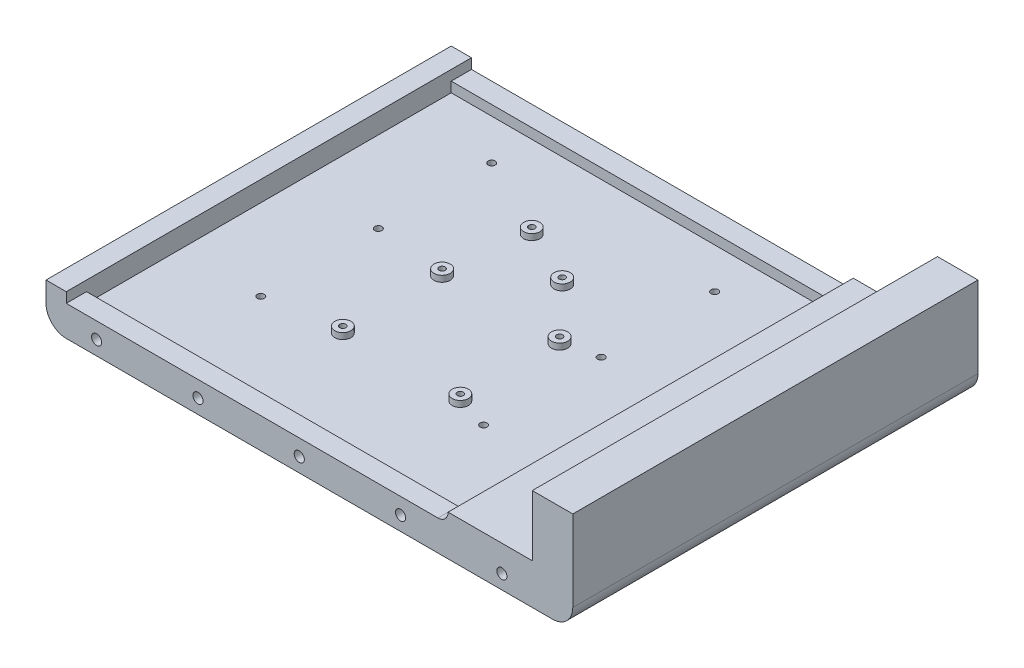
SolidWorks part; units mm, degrees
ref_plane "前视基准面" through (0, 0, 0) normal (0, 0, 1) x (1, 0, 0)
ref_plane "上视基准面" through (0, 0, 0) normal (0, 1, 0) x (1, 0, 0)
ref_plane "右视基准面" through (0, 0, 0) normal (1, 0, 0) x (0, 0, -1)
other "Configuration Table"
sketch "草图1" plane through (0, 0, 0) normal (0, 0, 1) x (1, 0, 0)
  line L0 (-120, 0) -> (120, 0)
  line L1 (130, 10) -> (130, 49.9853)
  line L3 (-130, 20) -> (-130, 10)
  line L6 (-110, 20) -> (110, 20)
  line L7 (110, 20) -> (110, 48.0385)
  line L10 (-110, 20) -> (-130, 20)
  line L11 (130, 49.9853) -> (130, 50)
  line L20 (130, 50) -> (110, 50)
  line L21 (110, 50) -> (110, 48.0385)
  arc A1 (-120, 0) -> (-130, 10) centre (-120, 10) cw
  arc A2 (120, 0) -> (130, 10) centre (120, 10) ccw
  point P15 (0, 0)
  dimension "D2" = 260
  dimension "D3" = 10
  dimension "D4" = 10
  dimension "D5" = 20
  dimension "D1" = 50
extrude "凸台-拉伸1" add sketch "草图1" along normal blind 200
sketch "草图3" plane through (0, 0, 200) normal (0, 0, 1) x (1, 0, 0)
  line L14 (-120, 20) -> (68.453, 20)
  line L15 (-115, 15) -> (120, 15)
  line L16 (-115, 20) -> (-115, 15)
  line L17 (-120, 15) -> (63.453, 15)
  line L18 (130, 10) -> (130, 50) construction
  line L19 (110, 20) -> (-130, 20) construction
  line L20 (-130, 20) -> (-130, 10) construction
  line L21 (-120, 15) -> (-120, 20)
  arc A10 (68.453, 20) -> (63.453, 15) centre (63.453, 20) cw
  dimension "D2" = 10
  dimension "D3" = 61.547
  dimension "D4" = 5
  dimension "D1" = 15
extrude "切除-拉伸1" cut sketch "草图3" against normal up to next
sketch "草图4" plane through (0, 15, 0) normal (0, 1, 0) x (1, 0, 0)
  line L0 (30, -30) -> (-80, -30) construction
  line L1 (-80, -30) -> (-80, -86) construction
  line L2 (-80, -86) -> (30, -86) construction
  line L3 (30, -86) -> (30, -30) construction
  line L4 (-80, -86) -> (-80, -144) construction
  line L5 (-80, -144) -> (30, -144) construction
  line L6 (30, -144) -> (30, -86) construction
  line L7 (13.911, -90.416) -> (-44.089, -90.416) construction
  line L8 (-44.089, -90.416) -> (-44.089, -139.416) construction
  line L9 (-44.089, -139.416) -> (13.911, -139.416) construction
  line L10 (13.911, -139.416) -> (13.911, -90.416) construction
  line L11 (-120, 0) -> (63.453, 0) construction
  line L13 (-130, -200) -> (-130, 0) construction
  circle A27 centre (30, -30) radius 1.75
  circle A29 centre (30, -86) radius 1.75
  circle A30 centre (30, -144) radius 1.75
  circle A31 centre (-80, -144) radius 1.75
  circle A32 centre (-80, -86) radius 1.75
  circle A33 centre (-80, -30) radius 1.75
  circle A34 centre (-10.76, -64.486) radius 1.5
  circle A35 centre (-39.76, -50.486) radius 1.5
  circle A36 centre (-44.089, -90.416) radius 1.5
  circle A37 centre (13.911, -90.416) radius 1.5
  circle A38 centre (13.911, -139.416) radius 1.5
  circle A39 centre (-44.089, -139.416) radius 1.5
  dimension "D1" = 3.5
  dimension "D13" = 3
  dimension "D14" = 3
  dimension "D17" = 3
  dimension "D18" = 3
  dimension "D19" = 3
  dimension "D20" = 3
  dimension "D2" = 110
  dimension "D3" = 56
  dimension "D4" = 58
  dimension "D5" = 49
  dimension "D6" = 58
  dimension "D7" = 4.584
  dimension "D8" = 16.089
  dimension "D9" = 25.93
  dimension "D10" = 40.76
  dimension "D11" = 69.76
  dimension "D12" = 39.93
  dimension "D15" = 30
  dimension "D16" = 50
extrude "切除-拉伸2" cut sketch "草图4" against normal up to next
sketch "草图6" plane through (0, 15, 0) normal (0, 1, 0) x (1, 0, 0)
  line L4 (-120, 0) -> (-120, -200)
  line L5 (-120, -200) -> (63.453, -200)
  line L6 (63.453, -200) -> (63.453, 0)
  line L7 (63.453, 0) -> (-120, 0)
  line L11 (63.453, 0) -> (-120, 0)
  line L20 (63.453, -10) -> (-120, -10)
  line L21 (-120, -200) -> (63.453, -200)
  line L23 (63.453, -200) -> (63.453, -10)
  line L24 (63.453, -10) -> (63.453, 0)
  line L25 (-120, -10) -> (-120, -200)
  line L26 (-120, 0) -> (-120, -10)
  line L27 (-120, -190) -> (63.453, -190)
  line L28 (-120, -10) -> (-120, -190)
  dimension "D2" = 10
  dimension "D1" = 0
  dimension "D3" = 10
extrude "切除-拉伸4" cut sketch "草图6" against normal offset from surface (5 mm away) 10
sketch "草图7" plane through (0, 10, 0) normal (0, 1, 0) x (1, 0, 0)
  circle A0 centre (-39.76, -50.486) radius 4
  circle A1 centre (-10.76, -64.486) radius 4
  circle A2 centre (13.911, -90.416) radius 4
  circle A3 centre (13.911, -139.416) radius 4
  circle A4 centre (-44.089, -139.416) radius 4
  circle A5 centre (-44.089, -90.416) radius 4
  circle A6 centre (-44.089, -139.416) radius 1.5 construction
  circle A7 centre (13.911, -139.416) radius 1.5 construction
  circle A8 centre (13.911, -90.416) radius 1.5 construction
  circle A9 centre (-10.76, -64.486) radius 1.5 construction
  circle A10 centre (-39.76, -50.486) radius 1.5 construction
  circle A11 centre (-44.089, -139.416) radius 1.5
  circle A12 centre (13.911, -139.416) radius 1.5
  circle A13 centre (13.911, -90.416) radius 1.5
  circle A14 centre (-10.76, -64.486) radius 1.5
  circle A15 centre (-39.76, -50.486) radius 1.5
  circle M7 centre (-39.76, -50.486) radius 1.5
  circle M11 centre (13.911, -90.416) radius 1.5
  circle M12 centre (-44.089, -139.416) radius 1.5
  circle M14 centre (13.911, -139.416) radius 1.5
  circle M16 centre (-10.76, -64.486) radius 1.5
  circle M17 centre (-44.089, -90.416) radius 1.5
  dimension "D1" = 8
  dimension "D2" = 8
  dimension "D3" = 8
  dimension "D4" = 8
  dimension "D5" = 8
  dimension "D6" = 8
extrude "凸台-拉伸2" add sketch "草图7" along normal blind 3 contours A0 M7 | A1 M16 | A2 M11 | A3 M14 | A4 M12 | A5 M17 | A15
sketch "草图8" plane through (0, 0, 0) normal (0, 0, -1) x (-1, 0, 0)
  circle A0 centre (105, 7) radius 2.5
  circle A1 centre (55, 7) radius 2.5
  circle A2 centre (5, 7) radius 2.5
  circle A3 centre (-45, 7) radius 2.5
  circle A4 centre (-95, 7) radius 2.5
extrude "切除-拉伸5" cut sketch "草图8" against normal blind 15
ref_plane "基准面1" through (0, 0, 100) normal (0, 0, -1) x (-1, 0, 0)
mirror "镜向1" about plane through (0, 0, 100) normal (0, 0, -1) of "切除-拉伸5"
sketch "草图9" plane through (0, 0, 0) normal (0, -1, 0) x (1, 0, 0)
  circle A0 centre (-80, 144) radius 3.5
  circle A1 centre (30, 144) radius 3.5
  circle A2 centre (30, 86) radius 3.5
  circle A3 centre (30, 30) radius 3.5
  circle A4 centre (-80, 30) radius 3.5
  circle A5 centre (-80, 86) radius 3.5
  dimension "D1" = 7
extrude "切除-拉伸6" cut sketch "草图9" against normal offset from surface (5 mm away) 5 up to face at (-48.089, 10, 90.416)
sketch "草图10" plane through (0, 0, 0) normal (0, -1, 0) x (1, 0, 0)
  line L0 (-27.5, 100) -> (27.5, 100) construction
  point P2 (0, 100)
